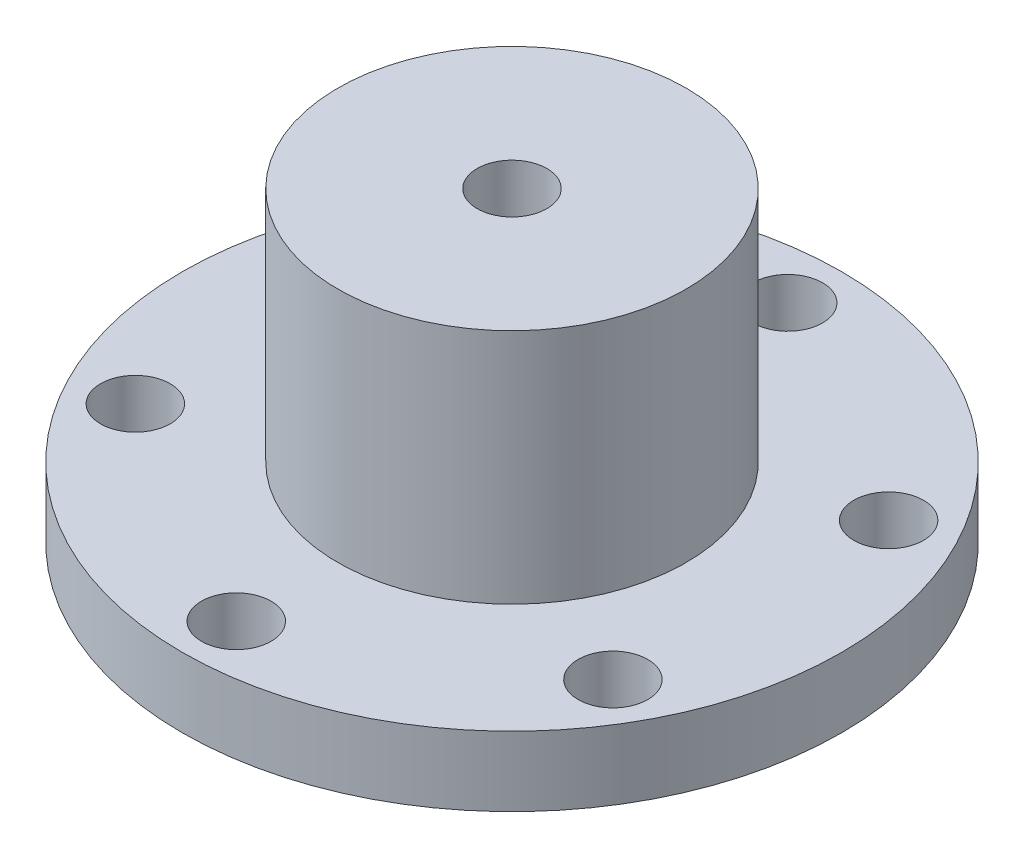
SolidWorks part; units mm, degrees
ref_plane "Front Plane" through (0, 0, 0) normal (0, 0, 1) x (1, 0, 0)
ref_plane "Top Plane" through (0, 0, 0) normal (0, 1, 0) x (1, 0, 0)
ref_plane "Right Plane" through (0, 0, 0) normal (1, 0, 0) x (0, 0, -1)
sketch "Sketch1" plane through (0, 0, 0) normal (1, 0, 0) x (0, 0, -1)
  line L0 (0, 0) -> (0, 26.4) construction
  line L1 (-3, 0) -> (-28.4, 0)
  line L2 (-28.4, 0) -> (-28.4, 6)
  line L3 (-28.4, 6) -> (-15, 6)
  line L4 (-15, 6) -> (-15, 26.4)
  line L5 (-15, 26.4) -> (-3, 26.4)
  line L6 (-3, 26.4) -> (-3, 0)
  dimension "D1" = 3
  dimension "D2" = 28.4
  dimension "D3" = 26.4
  dimension "D4" = 20.4
  dimension "D5" = 15
revolve "Revolve1" add sketch "Sketch1" angle 360 about L0
sketch "Sketch2" plane through (0, 6, 0) normal (0, 1, 0) x (1, 0, 0)
  line L0 (0, 0) -> (0, 23.75) construction
  circle A0 centre (0, 23.75) radius 3
  circle A1 centre (20.5681, 11.875) radius 3
  circle A2 centre (20.5681, -11.875) radius 3
  circle A3 centre (0, -23.75) radius 3
  circle A4 centre (-20.5681, -11.875) radius 3
  circle A5 centre (-20.5681, 11.875) radius 3
  point P16 (0, 0)
  dimension "D1" = 6
  dimension "D2" = 23.75
  dimension "D3" = 6
extrude "Cut-Extrude1" cut sketch "Sketch2" against normal through all
